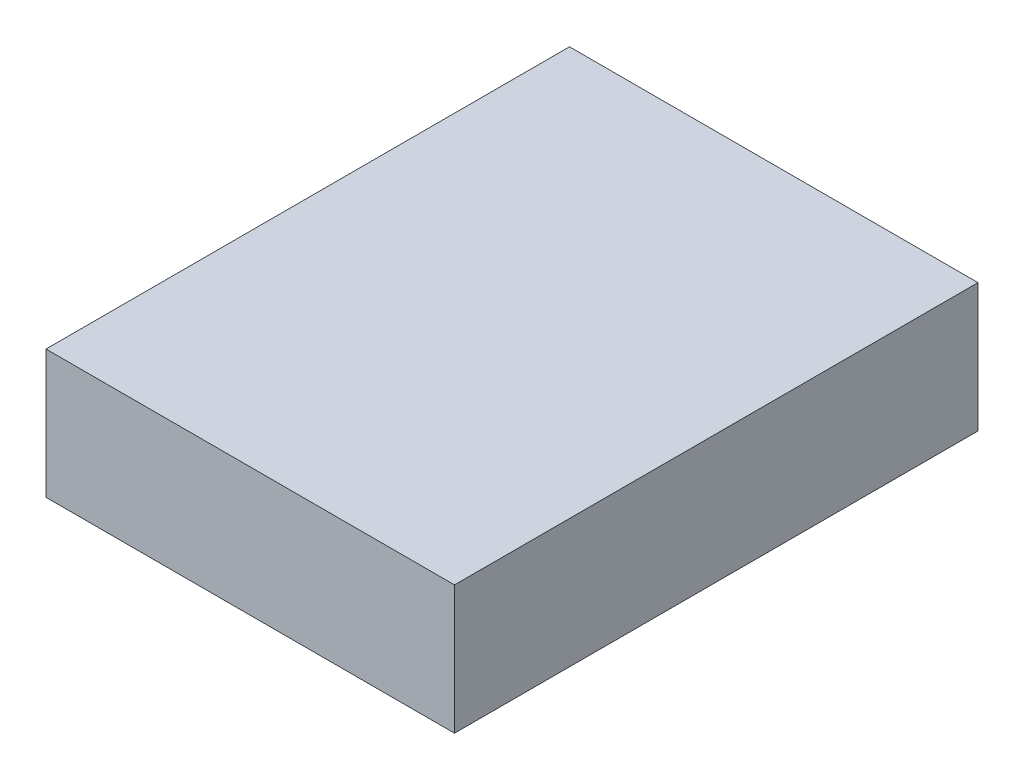
SolidWorks part; units mm, degrees
ref_plane "Front" through (0, 0, 0) normal (0, 0, 1) x (1, 0, 0)
ref_plane "Top" through (0, 0, 0) normal (0, 1, 0) x (1, 0, 0)
ref_plane "Right" through (0, 0, 0) normal (1, 0, 0) x (0, 0, -1)
other "Configuration Table"
sketch "Sketch1" plane through (0, 0, 0) normal (0, 1, 0) x (1, 0, 0)
  line L1 (-31.8, 40.75) -> (31.8, 40.75)
  line L2 (-31.8, 40.75) -> (-31.8, -40.75)
  line L3 (-31.8, -40.75) -> (31.8, -40.75)
  line L4 (31.8, 40.75) -> (31.8, -40.75)
  line L5 (-31.8, 40.75) -> (31.8, -40.75) construction
  line L6 (-31.8, -40.75) -> (31.8, 40.75) construction
  point P0 (0, 0)
  dimension "D1" = 81.5
  dimension "D2" = 63.6
extrude "Boss-Extrude1" add sketch "Sketch1" along normal blind 20
